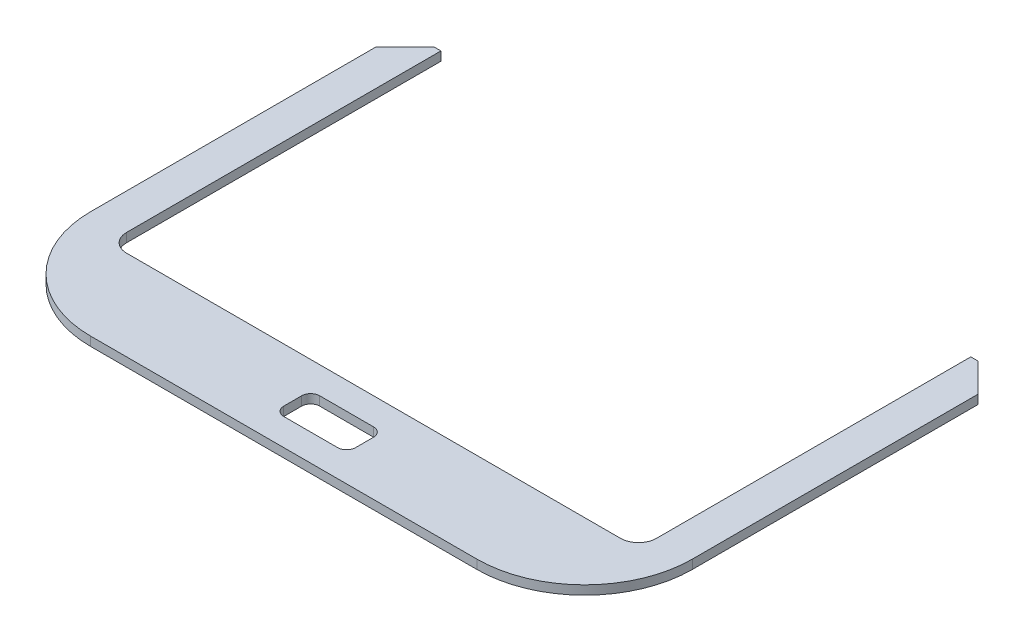
SolidWorks part; units mm, degrees
ref_plane "Front Plane" through (0, 0, 0) normal (0, 0, 1) x (1, 0, 0)
ref_plane "Top Plane" through (0, 0, 0) normal (0, 1, 0) x (1, 0, 0)
ref_plane "Right Plane" through (0, 0, 0) normal (1, 0, 0) x (0, 0, -1)
sketch "Sketch1" plane through (0, 0, 0) normal (0, 1, 0) x (1, 0, 0)
  line L0 (-46.8312, 58.7375) -> (-46.8312, 0)
  line L1 (-53.1812, 58.7375) -> (-46.8312, 58.7375)
  line L2 (-53.1812, 58.7375) -> (-53.1813, -15.875)
  line L3 (-53.1813, -15.875) -> (53.1813, -15.875)
  line L4 (53.1812, 58.7375) -> (53.1813, -15.875)
  line L5 (46.8312, 58.7375) -> (53.1812, 58.7375)
  line L6 (-53.1812, 58.7375) -> (53.1812, 58.7375) construction
  line L8 (46.8312, 58.7375) -> (46.8312, 0)
  line L10 (-46.8312, 0) -> (46.8312, 0)
  line L11 (-46.8312, 52.3875) -> (-46.8313, -9.525) construction
  line L13 (-46.8313, -9.525) -> (46.8313, -9.525) construction
  line L14 (46.8312, 52.3875) -> (46.8313, -9.525) construction
  line L15 (-46.8312, 52.3875) -> (46.8312, 52.3875) construction
  point P0 (0, 0)
  point P12 (0, 0)
  point P14 (0, -15.875)
  dimension "D1" = 6.35
  dimension "D2" = 74.6125
  dimension "D4" = 15.875
  dimension "D5" = 106.3625
  dimension "D3" = 93.6625
extrude "Boss-Extrude1" add sketch "Sketch1" along normal mid plane 1.5875
fillet "Fillet1" radius 19.05 2 edges at (53.1813, 0, 15.875) (-53.1813, 0, 15.875)
sketch "Sketch2" plane through (0, 0.7937, 0) normal (0, 1, 0) x (1, 0, 0)
  line L0 (0, 0) -> (0, -15.875) construction
  line L1 (46.8312, 0) -> (-46.8312, 0) construction
  line L2 (-34.1313, -15.875) -> (34.1313, -15.875) construction
  line L4 (-6.35, -4.7625) -> (6.35, -4.7625)
  line L5 (-6.35, -4.7625) -> (-6.35, -11.1125)
  line L6 (-6.35, -11.1125) -> (6.35, -11.1125)
  line L7 (6.35, -4.7625) -> (6.35, -11.1125)
  line L8 (-6.35, -4.7625) -> (6.35, -11.1125) construction
  line L9 (-6.35, -11.1125) -> (6.35, -4.7625) construction
  point P6 (0, -7.9375)
  dimension "D1" = 12.7
  dimension "D2" = 6.35
extrude "Cut-Extrude1" cut sketch "Sketch2" against normal through all both and the other way through all
fillet "Fillet2" radius 1.5875 4 edges at (6.35, 0, 11.1125) (6.35, 0, 4.7625) (-6.35, 0, 11.1125) (-6.35, 0, 4.7625)
chamfer "Chamfer1" distance 5.08 angle 45 2 edges at (53.1812, 0, -58.7375) (-53.1812, 0, -58.7375)
fillet "Fillet3" radius 3.175 2 edges at (46.8312, 0, 0) (-46.8312, 0, 0)
